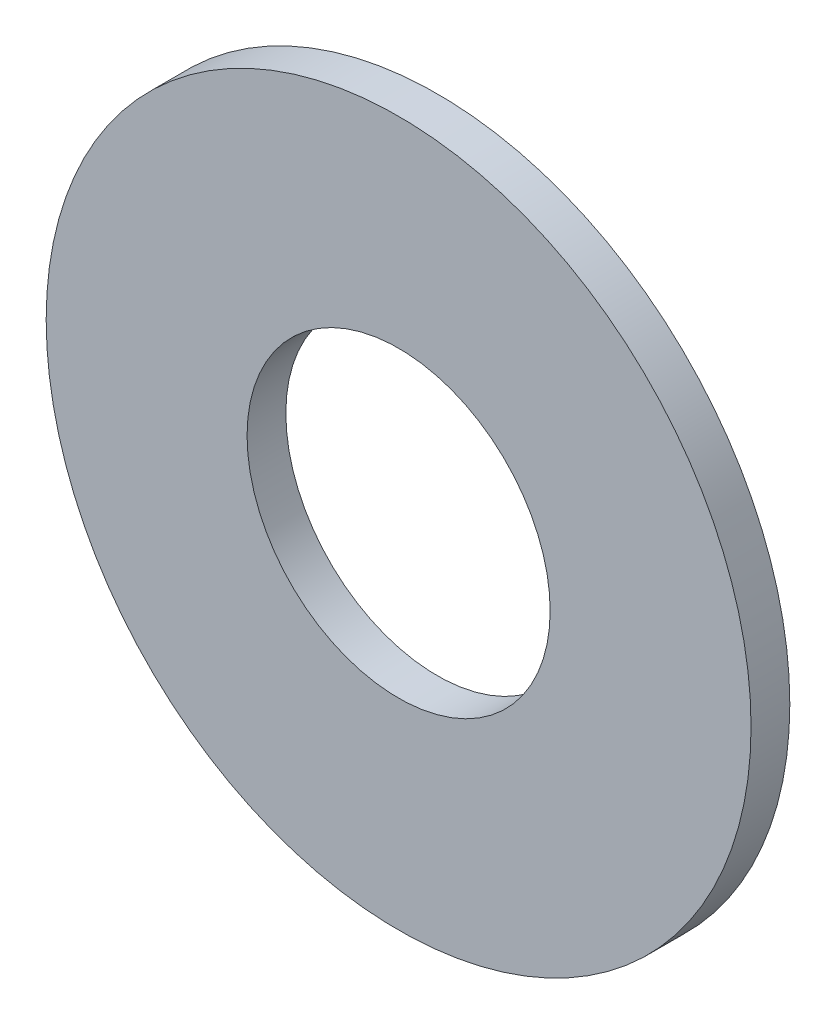
SolidWorks part; units mm, degrees
ref_plane "Front Plane" through (0, 0, 0) normal (0, 0, 1) x (1, 0, 0)
ref_plane "Top Plane" through (0, 0, 0) normal (0, 1, 0) x (1, 0, 0)
ref_plane "Right Plane" through (0, 0, 0) normal (1, 0, 0) x (0, 0, -1)
sketch "Sketch1" plane through (0, 0, 0) normal (0, 0, 1) x (1, 0, 0)
  circle A0 centre (0, 0) radius 12.7
  circle A1 centre (0, 0) radius 5.461
  dimension "D1" = 25.4
  dimension "D2" = 10.922
extrude "Boss-Extrude1" add sketch "Sketch1" along normal blind 1.397
